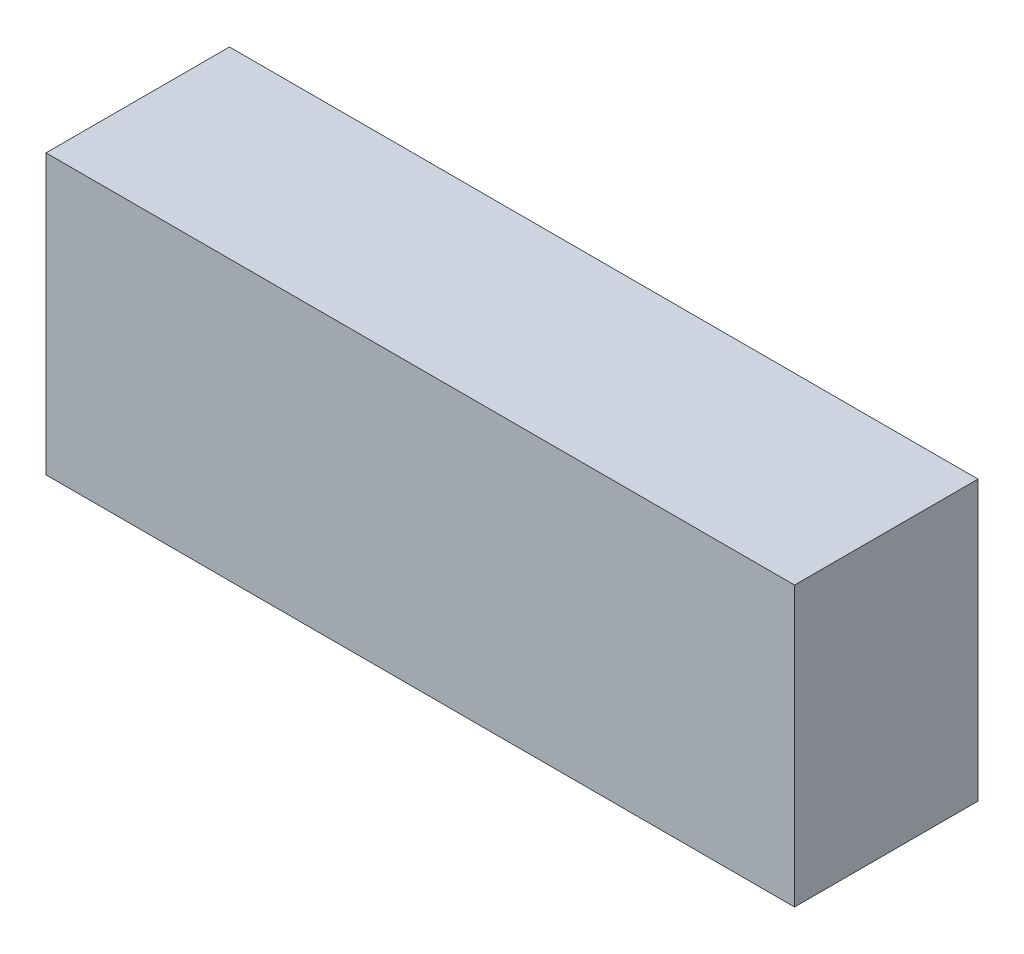
SolidWorks part; units mm, degrees
ref_plane "Front" through (0, 0, 0) normal (0, 0, 1) x (1, 0, 0)
ref_plane "Top" through (0, 0, 0) normal (0, 1, 0) x (1, 0, 0)
ref_plane "Right" through (0, 0, 0) normal (1, 0, 0) x (0, 0, -1)
sketch "Sketch1" plane through (0, 0, 0) normal (0, 0, 1) x (1, 0, 0)
  line L1 (0, 0) -> (102, 0)
  line L2 (0, 0) -> (0, 38)
  line L3 (0, 38) -> (102, 38)
  line L4 (102, 0) -> (102, 38)
  dimension "D1" = 102
  dimension "D2" = 38
extrude "Boss-Extrude1" add sketch "Sketch1" along normal blind 25
sketch "Sketch2" plane through (0, 0, 0) normal (-1, 0, 0) x (0, 0, 1)
  line L0 (12.5, 38) -> (12.5, 0) construction
  line L1 (25, 38) -> (0, 38) construction
  line L2 (50, 0) -> (-50, 0) construction
  circle A0 centre (12.5, 19) radius 3
  point P8 (0, 0)
  dimension "D1" = 6
extrude "Cut-Extrude1" cut sketch "Sketch2" against normal blind 60
hole_wizard "M4x0.7 Tapped Hole1" positions "Sketch3" profile "Sketch4" tap size "M4x0.7" standard "ANSI Metric"
sketch "Sketch3" plane through (0, 0, 0) normal (0, -1, 0) x (-1, 0, 0)
  line L0 (0, 50) -> (0, -50) construction
  line L1 (-12, -4) -> (-12, -21) construction
  line L2 (-12, -21) -> (-12, -12.5) construction
  line L3 (-12, -12.5) -> (0, -12.5) construction
  line L5 (0, -25) -> (0, 0) construction
  point P0 (-82, -4)
  point P2 (-12, -4)
  point P4 (-12, -21)
  point P6 (-82, -21)
  point P23 (0, 0)
  dimension "D1" = 12
  dimension "D2" = 70
  dimension "D3" = 17
sketch "Sketch4" plane through (82, 0, 4) normal (1, 0, 0) x (0, 0, -1)
  line L0 (0, 0) -> (0, 9.0914)
  line L1 (0, 9.0914) -> (1.65, 8.1)
  line L2 (1.65, 8.1) -> (1.65, 0.3147)
  line L3 (1.65, 0.3147) -> (2.025, 0)
  line L5 (2.025, 0) -> (0, 0)
  line L6 (-1.65, 0.3147) -> (-2.025, 0) construction
  line L10 (0, 9.0914) -> (-1.65, 8.1) construction
  line L11 (0, -6.35) -> (0, 107.95) construction
  dimension "Tap Drill Dia." = 3.3
  dimension "Tap Drill Depth" = 8.1
  dimension "Near C'Sink Dia." = 4.05
  dimension "Near C'Sink Angle" = 100
  dimension "Drill Angle" = 118
cosmetic thread "Hole Thread1" parameters "D1"=6, "D2"=4
cosmetic thread "Hole Thread2" parameters "D1"=6, "D2"=4
cosmetic thread "Hole Thread3" parameters "D1"=6, "D2"=4
cosmetic thread "Hole Thread4" parameters "D1"=6, "D2"=4
